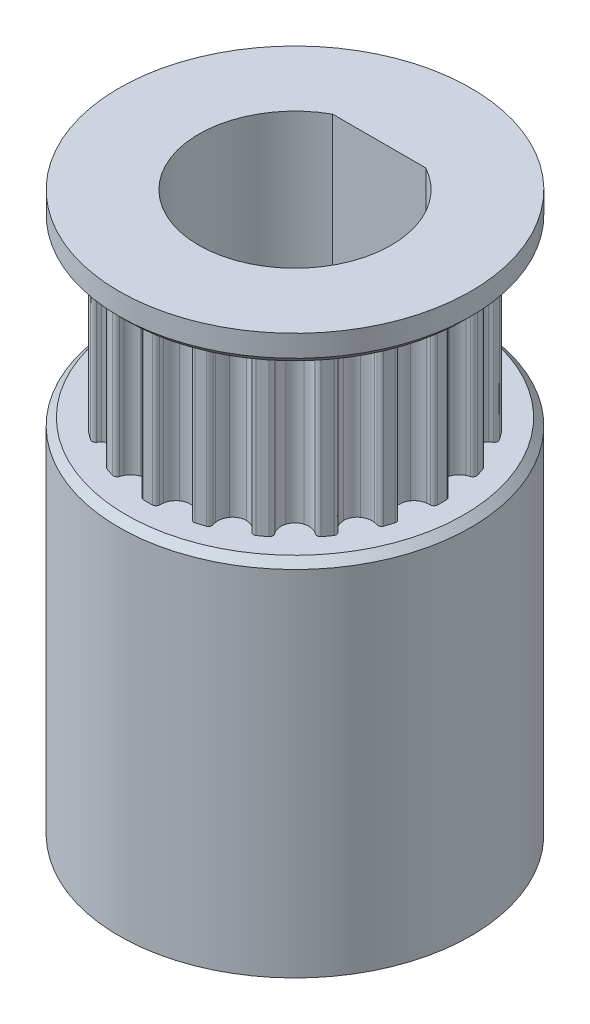
SolidWorks part; units mm, degrees
ref_plane "Front Plane" through (0, 0, 0) normal (0, 0, 1) x (1, 0, 0)
ref_plane "Top Plane" through (0, 0, 0) normal (0, 1, 0) x (1, 0, 0)
ref_plane "Right Plane" through (0, 0, 0) normal (1, 0, 0) x (0, 0, -1)
sketch "Sketch1" plane through (0, 0, 0) normal (0, 1, 0) x (1, 0, 0)
  line L0 (0, 0) -> (0, 6.3662) construction
  line L1 (0, 0) -> (0.9959, 6.2878) construction
  line L2 (0, 0) -> (1.3887, 6.2129) construction
  circle A0 centre (0, 0) radius 6.3662 construction
  circle A1 centre (0, 0) radius 5.3622 construction
  circle A2 centre (0, 0) radius 6.1122 construction
  arc A3 (0.8388, 5.2962) -> (0.5917, 5.401) centre (0.9257, 5.8443) cw
  arc A4 (0.3445, 5.8158) -> (0.3333, 5.9601) centre (1.3333, 5.965) cw
  circle A5 centre (0, 0) radius 5.9622 construction
  arc A6 (-0.188, 6.1093) -> (0.188, 6.1093) centre (0, 0) cw
  arc A7 (0.188, 6.1093) -> (0.3333, 5.9601) centre (0.1833, 5.9594) cw
  arc A8 (0.3445, 5.8158) -> (0.5917, 5.401) centre (0.9759, 5.9111) ccw
  arc A9 (-0.8388, 5.2962) -> (-0.5917, 5.401) centre (-0.9257, 5.8443) ccw
  arc A10 (-0.3445, 5.8158) -> (-0.5917, 5.401) centre (-0.9759, 5.9111) cw
  arc A11 (-0.3445, 5.8158) -> (-0.3333, 5.9601) centre (-1.3333, 5.965) ccw
  arc A12 (-0.188, 6.1093) -> (-0.3333, 5.9601) centre (-0.1833, 5.9594) ccw
  arc A13 (-0.8388, 5.2962) -> (0.8388, 5.2962) centre (0, 0) cw
  point P13 (1.3333, 5.965)
  point P16 (0, 6.1122)
  dimension "D1" = 12.7324
  dimension "D6" = 0.555
  dimension "D7" = 1
  dimension "D9" = 0.15
  dimension "D2" = 9
  dimension "D3" = 3.6
  dimension "D4" = 1.004
  dimension "D5" = 0.75
  dimension "D8" = 0.15
extrude "Boss-Extrude1" add sketch "Sketch1" along normal blind 7 contours A9 A13 A3 A8 A4 A7 A6 A12 A11 A10
sketch "Sketch2" plane through (0, 0, 0) normal (0, -1, 0) x (1, 0, 0)
  circle A0 centre (0, 0) radius 5.3622
  arc A2 (-0.8388, -5.2962) -> (0.8388, -5.2962) centre (0, 0) ccw construction
  arc A5 (-0.8388, -5.2962) -> (0.8388, -5.2962) centre (0, 0) ccw
  arc M3 (-0.8388, -5.2962) -> (-0.5917, -5.401) centre (-0.9257, -5.8443) cw
  arc M4 (-0.5917, -5.401) -> (-0.3445, -5.8158) centre (-0.9759, -5.9111) cw
  arc M5 (-0.3445, -5.8158) -> (-0.3333, -5.9601) centre (-1.3333, -5.965) cw
  arc M6 (-0.3333, -5.9601) -> (-0.188, -6.1093) centre (-0.1833, -5.9594) ccw
  arc M7 (-0.188, -6.1093) -> (0.188, -6.1093) centre (0, 0) ccw
  arc M8 (0.188, -6.1093) -> (0.3333, -5.9601) centre (0.1833, -5.9594) ccw
  arc M9 (0.3333, -5.9601) -> (0.3445, -5.8158) centre (1.3333, -5.965) cw
  arc M10 (0.3445, -5.8158) -> (0.5917, -5.401) centre (0.9759, -5.9111) cw
  arc M11 (0.5917, -5.401) -> (0.8388, -5.2962) centre (0.9257, -5.8443) cw
  arc M12 (0.8388, -5.2962) -> (-0.8388, -5.2962) centre (0, 0) cw
extrude "Boss-Extrude2" add sketch "Sketch2" against normal blind 7 contours A0 M3 M12 M11 M10 M9 M8 M7 M6 M5 M4
pattern_circular "CirPattern3" count 20 over 360 about axis through (0, 0, 0) along (0, 1, 0) of "Boss-Extrude1"
sketch "Sketch3" plane through (0, 7, 0) normal (0, 1, 0) x (1, 0, 0)
  circle A0 centre (0, 0) radius 7.3122
  arc A3 (0.2249, 7.3087) -> (-0.2249, 7.3087) centre (0, 0) ccw
  arc A4 (0.2249, 7.3087) -> (-0.2249, 7.3087) centre (0, 0) ccw
  dimension "D1" = 1.2
extrude "Boss-Extrude3" add sketch "Sketch3" along normal blind 1.2 contours A0
sketch "Sketch4" plane through (0, 0, 0) normal (0, -1, 0) x (1, 0, 0)
  circle A0 centre (0, 0) radius 7.3122 construction
  circle A1 centre (0, 0) radius 7.3122
extrude "Boss-Extrude4" add sketch "Sketch4" along normal blind 15
sketch "Sketch5" plane through (0, 8.2, 0) normal (0, 1, 0) x (1, 0, 0)
  line L0 (-1.9365, 3.5) -> (1.9365, 3.5)
  arc A0 (-1.9365, 3.5) -> (1.9365, 3.5) centre (0, 0) ccw
  dimension "D1" = 8
  dimension "D2" = 3.5
extrude "Cut-Extrude1" cut sketch "Sketch5" against normal through all contours L0 A0
chamfer "Chamfer1" distance 0.3 angle 45 2 edges at (0, 7, 7.3122) (0, 0, -7.3122)
equation "\"TeethNumber\"= 20"
equation "\"Pitch\"= 2"
equation "\"PullyDiameter\"= \"TeethNumber\" * \"Pitch\" / PI"
equation "\"ToothAngle\"= ( 360 / \"TeethNumber\" ) * 1deg"
equation "\"TransOffsetAngle\"= \"ToothAngle\" * 0.2' "
equation "\"ShoulderRadius\"= 0.15"
equation "\"RootRadius\"= 0.555"
equation "\"TransRadius\"= 1"
equation "\"ToothHeight\"= 0.75"
equation "\"PLD\"= 0.254"
equation "\"D1@Sketch1\"=\"PullyDiameter\""
equation "\"D2@Sketch1\"=\"ToothAngle\"/2"
equation "\"D3@Sketch1\"=\"TransOffsetAngle\""
equation "\"D4@Sketch1\"=\"PLD\"+\"ToothHeight\""
equation "\"D5@Sketch1\"=\"ToothHeight\""
equation "\"D6@Sketch1\" = \"RootRadius\""
equation "\"D7@Sketch1\"=\"TransRadius\""
equation "\"D9@Sketch1\"=\"ShoulderRadius\""
